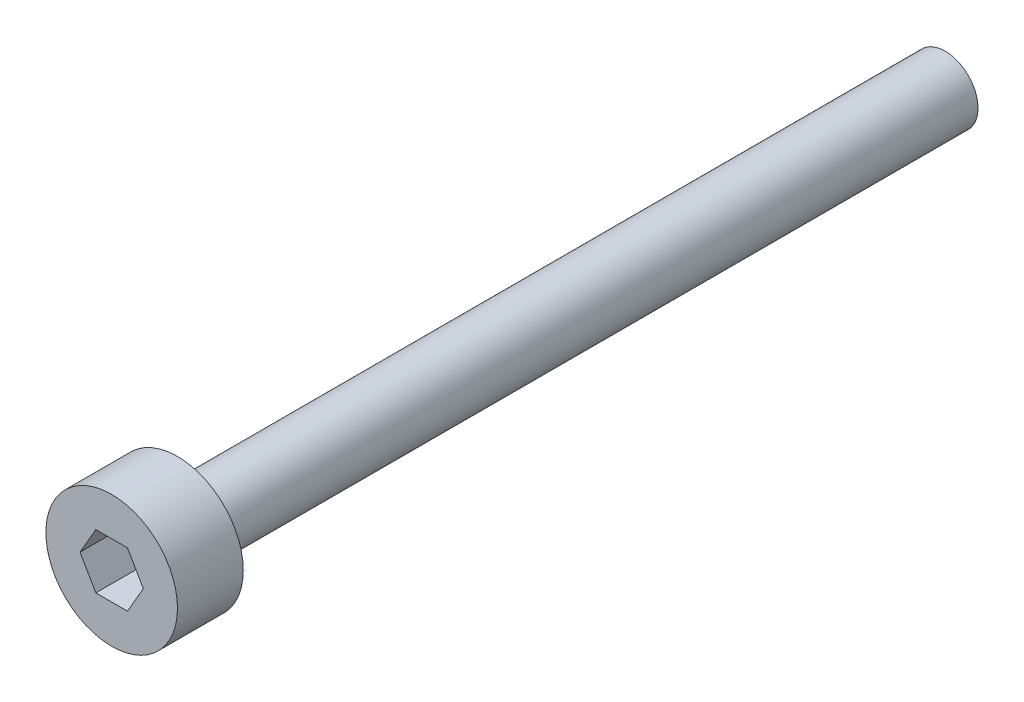
SolidWorks part; units mm, degrees
ref_plane "正面" through (0, 0, 0) normal (0, 0, 1) x (1, 0, 0)
ref_plane "平面" through (0, 0, 0) normal (0, 1, 0) x (1, 0, 0)
ref_plane "右側面" through (0, 0, 0) normal (1, 0, 0) x (0, 0, -1)
sketch "ｽｹｯﾁ5" plane through (0, 0, 0) normal (0, 0, 1) x (1, 0, 0)
  circle A0 centre (0, 0) radius 3
  dimension "D1" = 6
extrude "ﾎﾞｽ - 押し出し1" add sketch "ｽｹｯﾁ5" along normal blind 3
sketch "ｽｹｯﾁ6" plane through (0, 0, 3) normal (0, 0, 1) x (1, 0, 0)
  line L1 (1.4434, 0) -> (0.7217, 1.25)
  line L2 (0.7217, 1.25) -> (-0.7217, 1.25)
  line L3 (-0.7217, 1.25) -> (-1.4434, 0)
  line L4 (-1.4434, 0) -> (-0.7217, -1.25)
  line L5 (-0.7217, -1.25) -> (0.7217, -1.25)
  line L6 (0.7217, -1.25) -> (1.4434, 0)
  circle A0 centre (0, 0) radius 1.25 construction
  dimension "D1" = 2.5
extrude "ｶｯﾄ - 押し出し1" cut sketch "ｽｹｯﾁ6" against normal blind 2
sketch "ｽｹｯﾁ7" plane through (0, 0, 0) normal (0, 0, -1) x (-1, 0, 0)
  circle A0 centre (0, 0) radius 1.5
  dimension "D1" = 3
extrude "ﾎﾞｽ - 押し出し2" add sketch "ｽｹｯﾁ7" along normal blind 35
